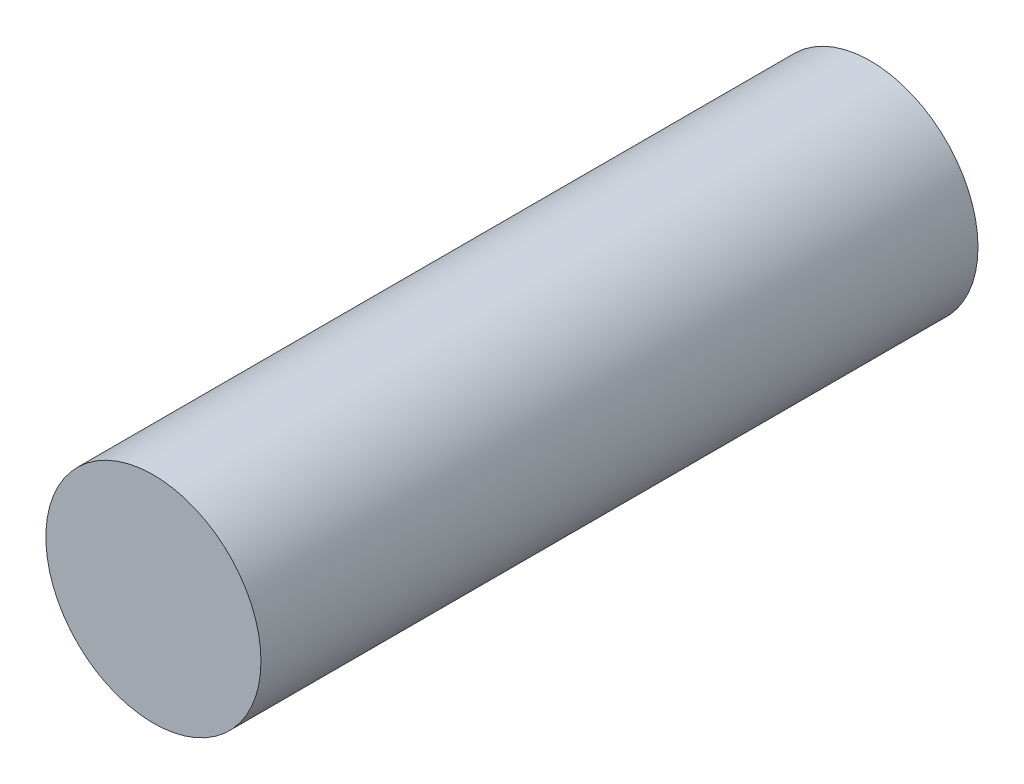
SolidWorks part; units mm, degrees
material "Rubber"
ref_plane "Front Plane" through (0, 0, 0) normal (0, 0, 1) x (1, 0, 0)
ref_plane "Top Plane" through (0, 0, 0) normal (0, 1, 0) x (1, 0, 0)
ref_plane "Right Plane" through (0, 0, 0) normal (1, 0, 0) x (0, 0, -1)
sketch "Sketch1" plane through (0, 0, 0) normal (0, 0, 1) x (1, 0, 0)
  circle A0 centre (0, 0) radius 1.5
  dimension "D1" = 3
extrude "Boss-Extrude1" add sketch "Sketch1" along normal blind 10
sketch "Sketch2" plane through (0, 0, 0) normal (0, 0, -1) x (-1, 0, 0)
  circle A0 centre (0, 0) radius 0.7937
  dimension "D1" = 1.5875
extrude "Cut-Extrude1" cut sketch "Sketch2" against normal blind 3.5
